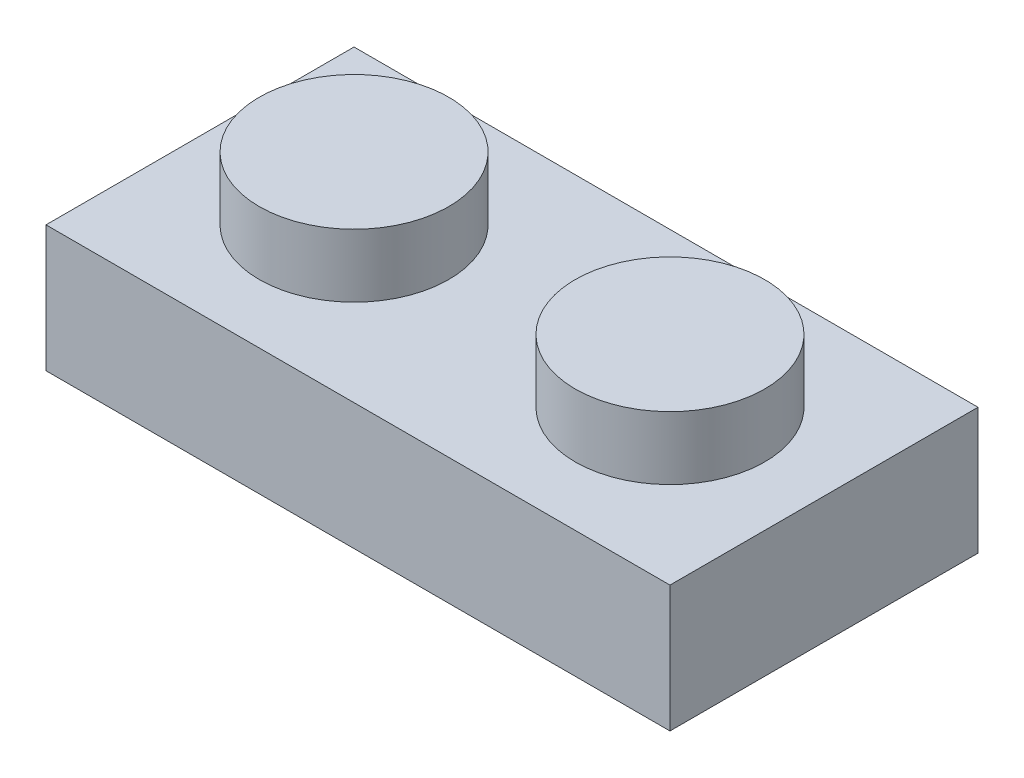
SolidWorks part; units mm, degrees
material "ABS"
ref_plane "Front Plane" through (0, 0, 0) normal (0, 0, 1) x (1, 0, 0)
ref_plane "Top Plane" through (0, 0, 0) normal (0, 1, 0) x (1, 0, 0)
ref_plane "Right Plane" through (0, 0, 0) normal (1, 0, 0) x (0, 0, -1)
sketch "Sketch1" plane through (0, 0, 0) normal (0, 0, 1) x (1, 0, 0)
  line L1 (0, 0) -> (15.8, 0)
  line L2 (0, 0) -> (0, 3.2)
  line L3 (0, 3.2) -> (15.8, 3.2)
  line L4 (15.8, 0) -> (15.8, 3.2)
  dimension "D1" = 3.2
  dimension "D2" = 15.8
extrude "Boss-Extrude1" add sketch "Sketch1" against normal blind 7.8
sketch "Sketch2" plane through (0, 3.2, 0) normal (0, 1, 0) x (1, 0, 0)
  line L0 (0, 7.8) -> (0, 0) construction
  line L1 (15.8, 0) -> (0, 0) construction
  circle A0 centre (3.9, 3.9) radius 2.4
  dimension "D1" = 4.8
  dimension "D2" = 3.9
  dimension "D3" = 3.9
extrude "Boss-Extrude2" add sketch "Sketch2" along normal blind 1.6 contours A0
pattern_linear "LPattern1" count 2 spacing 8 along (0, 0, 1) count 6 spacing 8 along (1, 0, 0) of "Boss-Extrude2"
shell "Shell1" thickness 1.2
sketch "Sketch3" plane through (0, 2, 0) normal (0, -1, 0) x (1, 0, 0)
  line L0 (0, 0) -> (15.8, 0) construction
  line L1 (15.8, -7.8) -> (15.8, 0) construction
  circle A0 centre (7.9, -3.9) radius 1.5
  circle A1 centre (7.9, -3.9) radius 0.6
  dimension "D1" = 3
  dimension "D2" = 1.2
  dimension "D3" = 3.9
  dimension "D4" = 7.9
extrude "Boss-Extrude3" add sketch "Sketch3" along normal offset from surface (1.8 mm away) 0.2 up to face at (7.9, 0, -3.9)
